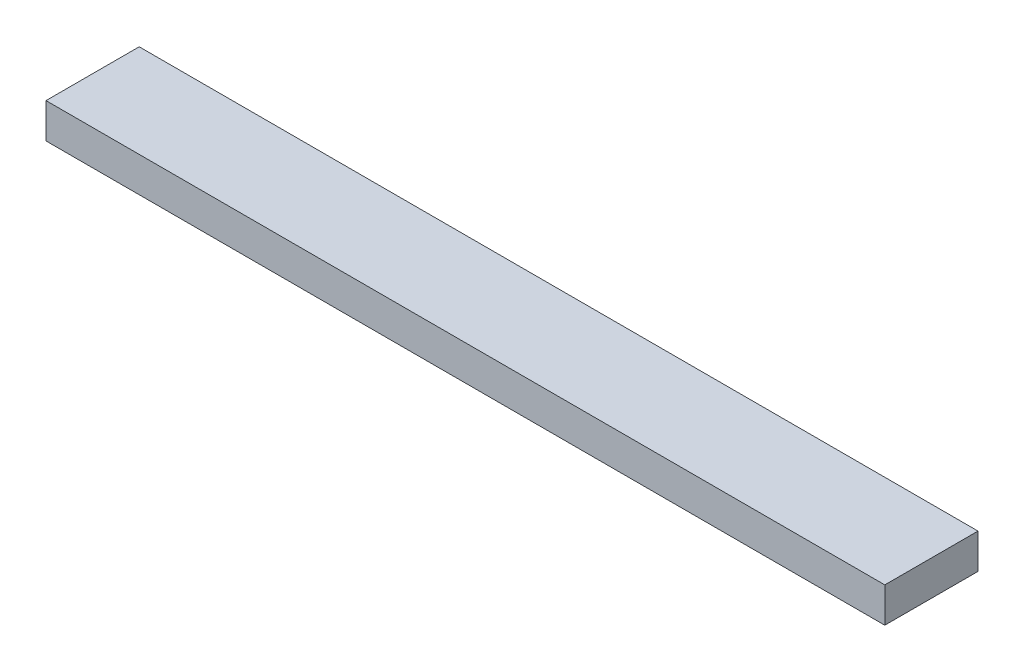
SolidWorks part; units mm, degrees
ref_plane "Front Plane" through (0, 0, 0) normal (0, 0, 1) x (1, 0, 0)
ref_plane "Top Plane" through (0, 0, 0) normal (0, 1, 0) x (1, 0, 0)
ref_plane "Right Plane" through (0, 0, 0) normal (1, 0, 0) x (0, 0, -1)
sketch "Sketch1" plane through (0, 0, 0) normal (0, 1, 0) x (1, 0, 0)
  line L1 (-228.6, -25.4) -> (228.6, -25.4)
  line L2 (-228.6, -25.4) -> (-228.6, 25.4)
  line L3 (-228.6, 25.4) -> (228.6, 25.4)
  line L4 (228.6, -25.4) -> (228.6, 25.4)
  line L5 (-228.6, -25.4) -> (228.6, 25.4) construction
  line L6 (-228.6, 25.4) -> (228.6, -25.4) construction
  point P0 (0, 0)
  dimension "D1" = 457.2
  dimension "D2" = 50.8
extrude "Boss-Extrude1" add sketch "Sketch1" along normal blind 19.05
